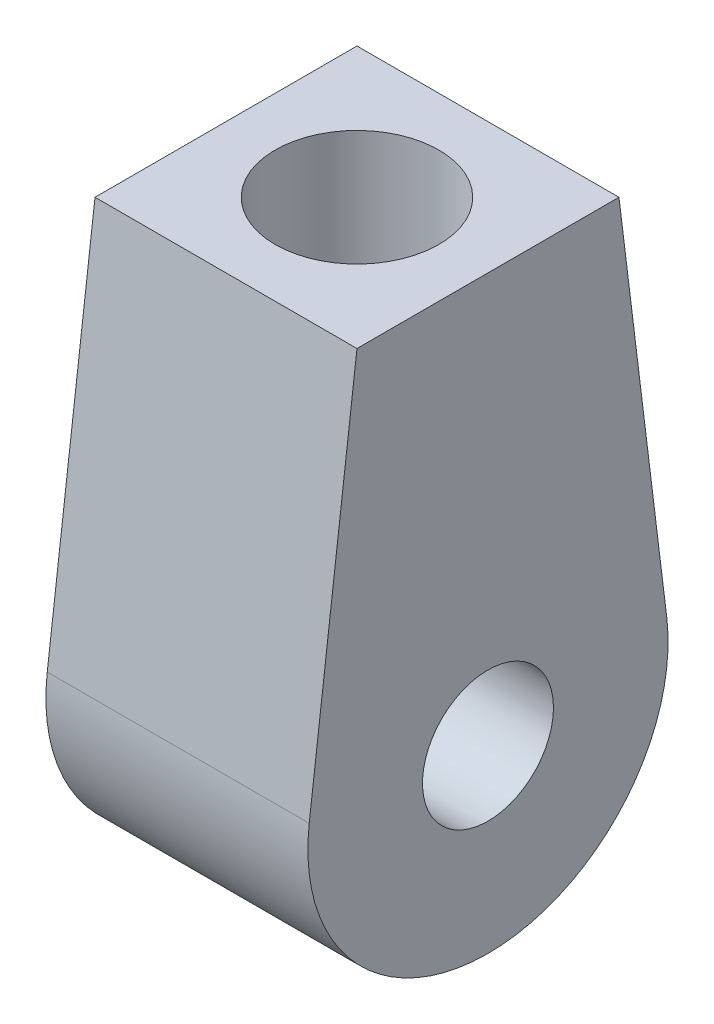
SolidWorks part; units mm, degrees
ref_plane "Ön Düzlem" through (0, 0, 0) normal (0, 0, 1) x (1, 0, 0)
ref_plane "Üst Düzlem" through (0, 0, 0) normal (0, 1, 0) x (1, 0, 0)
ref_plane "Sağ Düzlem" through (0, 0, 0) normal (1, 0, 0) x (0, 0, -1)
sketch "Çizim1" plane through (0, 0, 0) normal (1, 0, 0) x (0, 0, -1)
  line L0 (-74.6945, -11.3707) -> (-68.86, 35.9364)
  line L1 (-68.86, 35.9364) -> (-36.86, 35.9364)
  line L2 (-36.86, 35.9364) -> (-31.0015, -11.572)
  arc A0 (-74.6945, -11.3707) -> (-31.0015, -11.572) centre (-52.86, -14.0636) ccw
  circle A1 centre (-52.86, -14.0636) radius 8
  point P1 (-52.86, 35.9364)
  dimension "D1" = 44
  dimension "D4" = 16
  dimension "D2" = 32
  dimension "D3" = 50
extrude "Yükseklik-Ekstrüzyon1" add sketch "Çizim1" along normal blind 32
sketch "Çizim2" plane through (0, 35.9364, 0) normal (0, 1, 0) x (1, 0, 0)
  line L0 (32, -36.86) -> (32, -68.86) construction
  line L1 (32, -36.86) -> (0, -36.86) construction
  circle A0 centre (16, -52.86) radius 10
  dimension "D1" = 20
  dimension "D2" = 16
  dimension "D3" = 16
extrude "Kes-Ekstrüzyon1" cut sketch "Çizim2" against normal blind 38
